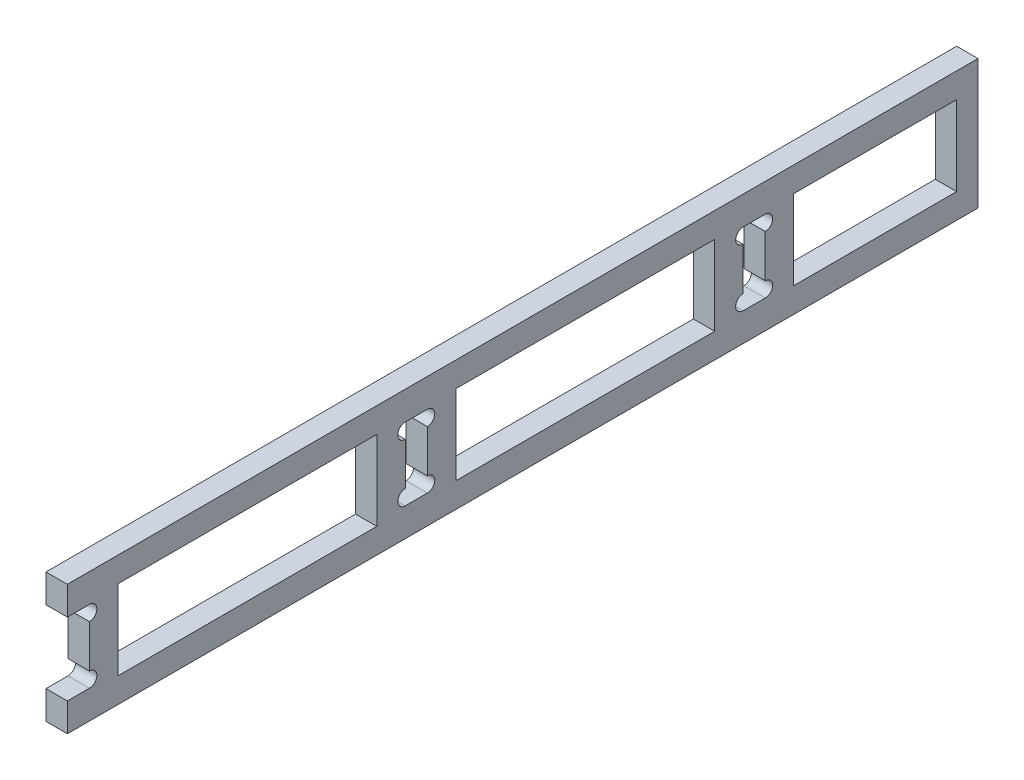
SolidWorks part; units mm, degrees
material "玻纤板"
ref_plane "前视基准面" through (0, 0, 0) normal (0, 0, 1) x (1, 0, 0)
ref_plane "上视基准面" through (0, 0, 0) normal (0, 1, 0) x (1, 0, 0)
ref_plane "右视基准面" through (0, 0, 0) normal (1, 0, 0) x (0, 0, -1)
sketch "草图1" plane through (0, 0, 0) normal (1, 0, 0) x (0, 0, -1)
  line L0 (0, 0) -> (0, 15.8388) construction
  line L1 (1.55, -5.1) -> (-1.55, -5.1)
  line L2 (1.55, -5.1) -> (1.55, 5.1)
  line L3 (1.55, 5.1) -> (-1.55, 5.1)
  line L4 (-1.55, -5.1) -> (-1.55, 5.1)
  line L5 (1.55, -5.1) -> (-1.55, 5.1) construction
  line L6 (1.55, 5.1) -> (-1.55, -5.1) construction
  line L7 (-45.95, -5.1) -> (-49.05, -5.1)
  line L8 (-45.95, -5.1) -> (-45.95, 5.1)
  line L9 (-45.95, 5.1) -> (-49.05, 5.1)
  line L10 (-49.05, -5.1) -> (-49.05, 5.1) construction
  line L11 (-45.95, -5.1) -> (-49.05, 5.1) construction
  line L12 (-45.95, 5.1) -> (-49.05, -5.1) construction
  line L13 (49.05, -5.1) -> (45.95, -5.1)
  line L15 (49.05, 5.1) -> (45.95, 5.1)
  line L16 (45.95, -5.1) -> (45.95, 5.1)
  line L17 (49.05, -5.1) -> (45.95, 5.1) construction
  line L18 (49.05, 5.1) -> (45.95, -5.1) construction
  line L19 (5.55, 5.6) -> (41.95, 5.6)
  line L20 (49.05, -9.1) -> (-49.05, -9.1)
  line L21 (49.05, -9.1) -> (49.05, -5.1)
  line L22 (49.05, 9.1) -> (-49.05, 9.1)
  line L23 (-49.05, -9.1) -> (-49.05, -5.1)
  line L24 (49.05, -9.1) -> (-49.05, 9.1) construction
  line L25 (49.05, 9.1) -> (-49.05, -9.1) construction
  line L26 (-5.55, -5.6) -> (-41.95, -5.6)
  line L27 (-5.55, -5.6) -> (-5.55, 5.6)
  line L28 (-5.55, 5.6) -> (-41.95, 5.6)
  line L29 (-41.95, -5.6) -> (-41.95, 5.6)
  line L30 (-5.55, -5.6) -> (-41.95, 5.6) construction
  line L31 (-5.55, 5.6) -> (-41.95, -5.6) construction
  line L32 (41.95, -5.6) -> (41.95, 5.6)
  line L33 (5.55, -5.6) -> (41.95, -5.6)
  line L34 (5.55, -5.6) -> (5.55, 5.6)
  line L35 (-49.05, 5.1) -> (-49.05, 9.1)
  line L36 (49.05, 5.1) -> (49.05, 9.1)
  circle A0 centre (-45.95, 4.05) radius 1.05
  circle A1 centre (-45.95, -4.05) radius 1.05
  circle A4 centre (-1.55, 4.05) radius 1.05
  circle A5 centre (1.55, -4.05) radius 1.05
  circle A6 centre (1.55, 4.05) radius 1.05
  circle A7 centre (-1.55, -4.05) radius 1.05
  circle A8 centre (45.95, 4.05) radius 1.05
  circle A9 centre (45.95, -4.05) radius 1.05
  point P0 (0, 0)
  point P6 (-47.5, 0)
  point P11 (47.5, 0)
  point P34 (-23.75, 0)
  dimension "D4" = 2.1
  dimension "D1" = 95
  dimension "D2" = 3.1
  dimension "D3" = 10.2
  dimension "D6" = 4
  dimension "D7" = 4
  dimension "D8" = 3.5
  dimension "D9" = 4
extrude "凸台-拉伸1" add sketch "草图1" along normal blind 3
sketch "草图2" plane through (3, 0, 0) normal (1, 0, 0) x (0, 0, -1)
  line L2 (49.05, -9.1) -> (78.96, -9.1)
  line L3 (78.96, -9.1) -> (78.96, 9.1)
  line L4 (78.96, 9.1) -> (49.05, 9.1)
  line L6 (49.05, 5.1) -> (49.05, 9.1) construction
  line L7 (53.05, -5.6) -> (75.96, -5.6)
  line L8 (53.05, -5.6) -> (53.05, 5.6)
  line L9 (53.05, 5.6) -> (75.96, 5.6)
  line L10 (75.96, -5.6) -> (75.96, 5.6)
  line L11 (53.05, -5.6) -> (75.96, 5.6) construction
  line L12 (53.05, 5.6) -> (75.96, -5.6) construction
  line L13 (49.05, 9.1) -> (49.05, 5.1)
  line L14 (49.05, -9.1) -> (49.05, 5.1)
  circle A3 centre (49.05, 4.05) radius 1.05
  circle A4 centre (49.05, -4.05) radius 1.05
  arc A5 (45.95, -3) -> (45.95, -5.1) centre (45.95, -4.05) ccw construction
  point P17 (64.505, 0)
  line M30 (49.05, 5.1) -> (49.05, 9.1)
  line M40 (49.05, -9.1) -> (49.05, -5.1)
  dimension "D1" = 29.91
  dimension "D2" = 3.5
  dimension "D3" = 4
  dimension "D4" = 3
  dimension "D5" = 3.5
extrude "凸台-拉伸2" add sketch "草图2" along direction (1, 0, 0) on the side against the normal up to surface (3 mm away) contours A4 L2 L3 L4 A3 L14 L10 L7 L8 L9 M40 M30
